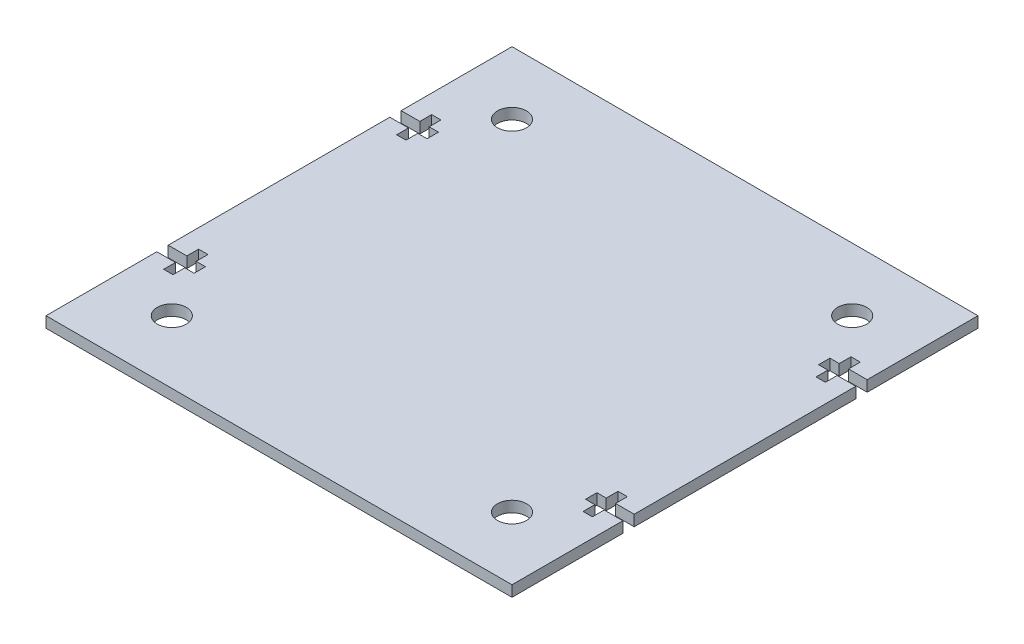
SolidWorks part; units mm, degrees
ref_plane "Front Plane" through (0, 0, 0) normal (0, 0, 1) x (1, 0, 0)
ref_plane "Top Plane" through (0, 0, 0) normal (0, 1, 0) x (1, 0, 0)
ref_plane "Right Plane" through (0, 0, 0) normal (1, 0, 0) x (0, 0, -1)
sketch "Sketch2" plane through (0, 0, 0) normal (0, 1, 0) x (1, 0, 0)
  line L0 (116.84, 95.25) -> (127, 95.25) construction
  line L1 (0, 0) -> (127, 0)
  line L2 (0, 0) -> (0, 127)
  line L3 (0, 127) -> (127, 127)
  line L4 (127, 0) -> (127, 127)
  line L21 (127, 96.7994) -> (116.84, 96.7994)
  line L26 (127, 96.7994) -> (127, 93.7006)
  line L27 (127, 93.7006) -> (116.84, 93.7006)
  line L28 (116.84, 96.7994) -> (116.84, 93.7006)
  line L29 (119.38, 90.4875) -> (121.92, 90.4875)
  line L30 (119.38, 90.4875) -> (119.38, 100.0125)
  line L31 (119.38, 100.0125) -> (121.92, 100.0125)
  line L32 (121.92, 90.4875) -> (121.92, 100.0125)
  line L33 (119.38, 90.4875) -> (121.92, 100.0125) construction
  line L34 (119.38, 100.0125) -> (121.92, 90.4875) construction
  line L35 (127, -63.5) -> (127, 63.5)
  line L36 (127, 33.2994) -> (116.84, 33.2994)
  line L37 (127, 33.2994) -> (127, 30.2006)
  line L38 (127, 30.2006) -> (116.84, 30.2006)
  line L39 (116.84, 33.2994) -> (116.84, 30.2006)
  line L40 (119.38, 26.9875) -> (121.92, 26.9875)
  line L41 (119.38, 26.9875) -> (119.38, 36.5125)
  line L42 (119.38, 36.5125) -> (121.92, 36.5125)
  line L43 (121.92, 26.9875) -> (121.92, 36.5125)
  line L44 (116.84, 31.75) -> (127, 31.75) construction
  line L45 (119.38, 26.9875) -> (121.92, 36.5125) construction
  line L46 (119.38, 36.5125) -> (121.92, 26.9875) construction
  line L47 (63.5, 127) -> (63.5, 0) construction
  line L48 (7.62, 36.5125) -> (5.08, 26.9875) construction
  line L49 (7.62, 26.9875) -> (5.08, 36.5125) construction
  line L50 (10.16, 31.75) -> (0, 31.75) construction
  line L51 (7.62, 100.0125) -> (5.08, 90.4875) construction
  line L52 (7.62, 90.4875) -> (5.08, 100.0125) construction
  line L53 (10.16, 95.25) -> (0, 95.25) construction
  line L54 (5.08, 26.9875) -> (5.08, 36.5125)
  line L55 (7.62, 36.5125) -> (5.08, 36.5125)
  line L56 (7.62, 26.9875) -> (7.62, 36.5125)
  line L57 (7.62, 26.9875) -> (5.08, 26.9875)
  line L58 (10.16, 33.2994) -> (10.16, 30.2006)
  line L59 (0, 30.2006) -> (10.16, 30.2006)
  line L60 (0, 33.2994) -> (0, 30.2006)
  line L61 (0, 33.2994) -> (10.16, 33.2994)
  line L62 (0, -63.5) -> (0, 63.5)
  line L63 (5.08, 90.4875) -> (5.08, 100.0125)
  line L64 (7.62, 100.0125) -> (5.08, 100.0125)
  line L65 (7.62, 90.4875) -> (7.62, 100.0125)
  line L66 (7.62, 90.4875) -> (5.08, 90.4875)
  line L67 (10.16, 96.7994) -> (10.16, 93.7006)
  line L68 (0, 93.7006) -> (10.16, 93.7006)
  line L69 (0, 96.7994) -> (0, 93.7006)
  line L70 (0, 96.7994) -> (10.16, 96.7994)
  point P9 (120.65, 95.25)
  point P23 (120.65, 31.75)
  point P53 (6.35, 31.75)
  point P54 (6.35, 95.25)
  dimension "D1" = 127
  dimension "D2" = 127
  dimension "D3" = 3.0988
  dimension "D4" = 10.16
  dimension "D5" = 2.54
  dimension "D6" = 9.525
  dimension "D7" = 5.08
  dimension "D8" = 31.75
  dimension "D9" = 2
extrude "Boss-Extrude1" add sketch "Sketch2" along normal blind 2.9718
sketch "Sketch3" plane through (0, 2.9718, 0) normal (0, 1, 0) x (1, 0, 0)
  line L0 (0, 0) -> (127, 0) construction
  line L1 (0, 0) -> (0, 30.2006) construction
  circle A0 centre (17.145, 109.855) radius 3.9688
  circle A1 centre (109.855, 109.855) radius 3.9687
  circle A2 centre (109.855, 17.145) radius 3.9687
  circle A3 centre (17.145, 17.145) radius 3.9688
  dimension "D1" = 7.9375
  dimension "D7" = 7.9375
  dimension "D8" = 7.9375
  dimension "D9" = 7.9375
  dimension "D2" = 92.71
  dimension "D3" = 92.71
  dimension "D4" = 92.71
  dimension "D5" = 17.145
  dimension "D6" = 17.145
extrude "Cut-Extrude1" cut sketch "Sketch3" against normal blind 2.9718
